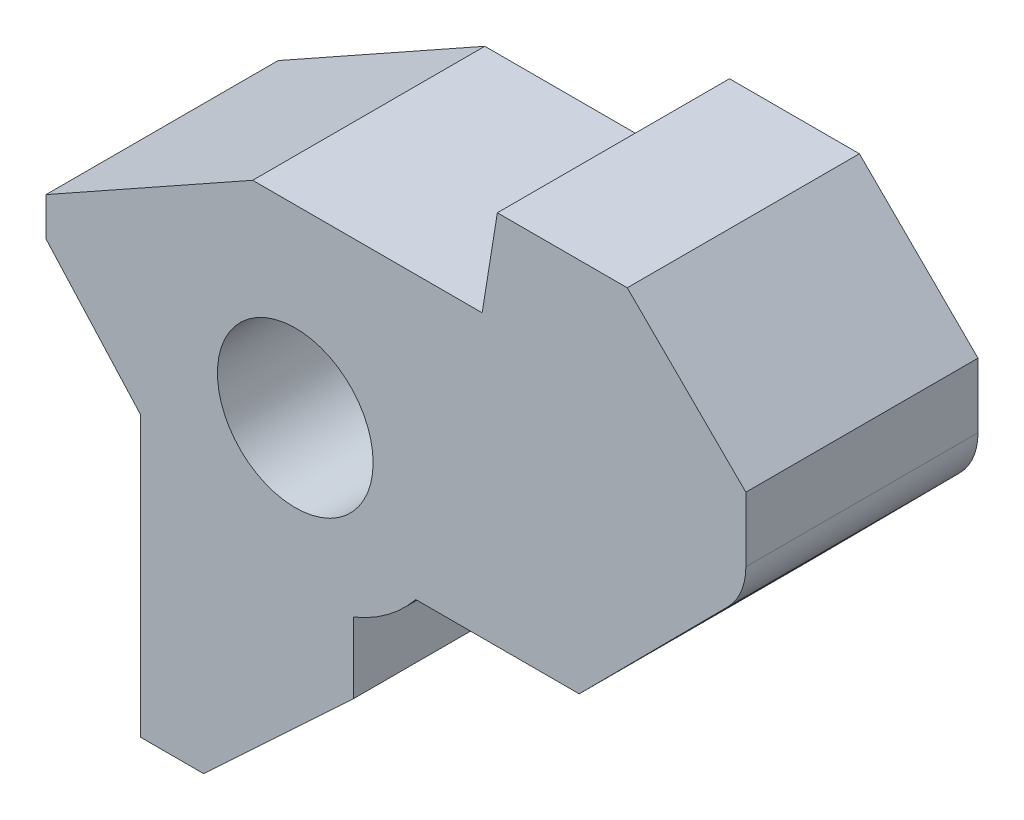
SolidWorks part; units mm, degrees
ref_plane "정면" through (0, 0, 0) normal (0, 0, 1) x (1, 0, 0)
ref_plane "윗면" through (0, 0, 0) normal (0, 1, 0) x (1, 0, 0)
ref_plane "우측면" through (0, 0, 0) normal (1, 0, 0) x (0, 0, -1)
sketch "스케치1" plane through (0, 0, 0) normal (0, 0, 1) x (1, 0, 0)
  line L0 (-5, -2.409) -> (-8.0531, 0.9786)
  line L1 (6.0379, 5.9574) -> (6.5286, 9.0015)
  line L2 (6.5286, 9.0015) -> (10.7256, 9.0015)
  line L3 (10.7256, 9.0015) -> (14.5571, 5.198)
  line L4 (14.5571, 5.198) -> (14.5571, 2.2863)
  line L5 (14.5571, 2.2863) -> (9.173, -3.1374)
  line L6 (9.173, -3.1374) -> (3.8932, -3.1374)
  line L7 (1.8761, -4.6347) -> (1.8761, -6.9239)
  line L8 (-2.9568, -11.4363) -> (-5, -11.4363)
  line L9 (-5, -11.4363) -> (-5, -2.409)
  line L10 (-2.9568, -11.4363) -> (1.8761, -6.9239)
  line L11 (6.0379, 5.9574) -> (-1.3764, 5.9574)
  line L12 (-2.9568, -11.4363) -> (-2.9568, -11.0363)
  line L13 (-8.0531, 0.9786) -> (-8.0531, 2.2192)
  line L14 (-8.0531, 2.2192) -> (-1.3764, 5.9574)
  circle A0 centre (0, 0) radius 2.515
  circle A1 centre (0, 0) radius 5
  dimension "D1" = 5.03
  dimension "D2" = 10
  dimension "D3" = 43.036
  dimension "D4" = 0.4
extrude "보스-돌출1" add sketch "스케치1" along normal blind 7.5
fillet "필렛1" radius 2 1 edges at (14.5571, 2.2863, 3.75)
